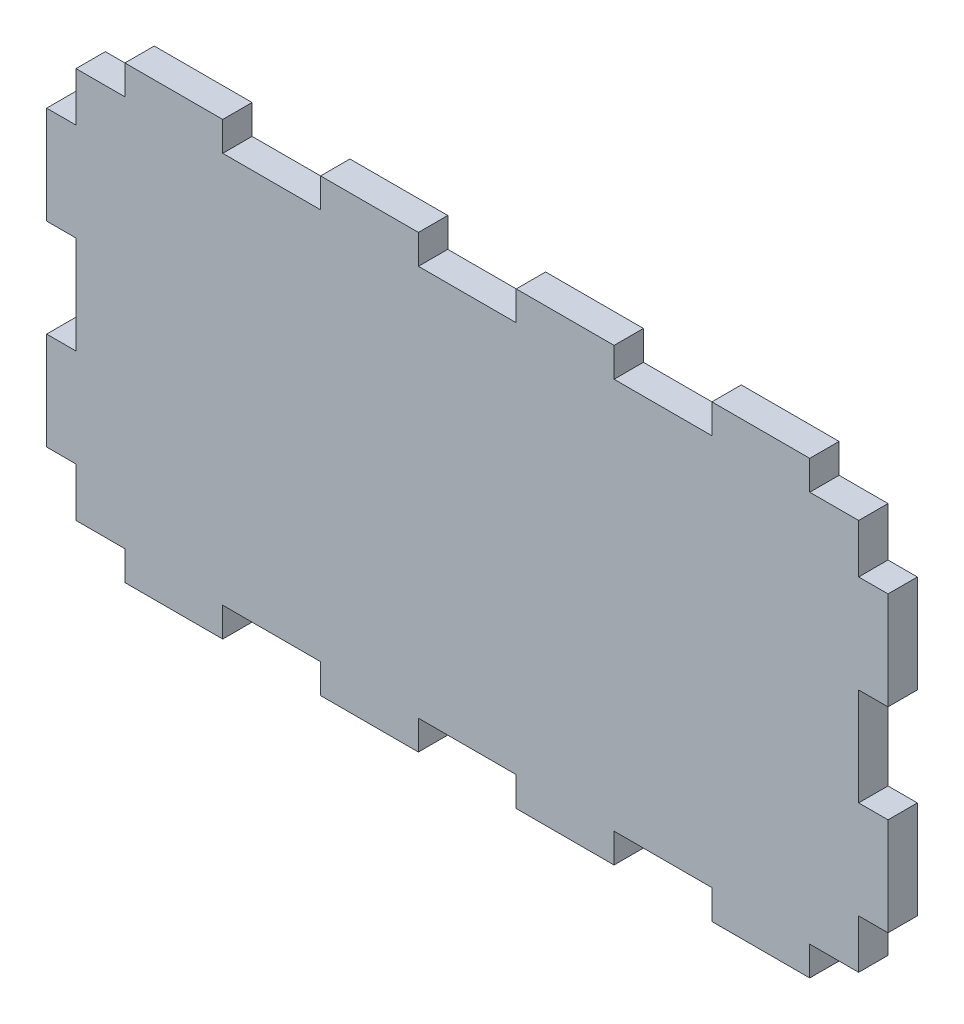
SolidWorks part; units mm, degrees
ref_plane "前视基准面" through (0, 0, 0) normal (0, 0, 1) x (1, 0, 0)
ref_plane "上视基准面" through (0, 0, 0) normal (0, 1, 0) x (1, 0, 0)
ref_plane "右视基准面" through (0, 0, 0) normal (1, 0, 0) x (0, 0, -1)
sketch "草图1" plane through (0, 0, 0) normal (0, 0, 1) x (1, 0, 0)
  line L0 (-15, -20) -> (-15, -23)
  line L1 (-40, 20) -> (-35, 20)
  line L2 (-40, 20) -> (-40, 15)
  line L3 (-40, -20) -> (-35, -20)
  line L4 (40, 20) -> (40, 15)
  line L5 (-40, 20) -> (40, -20) construction
  line L6 (-40, -20) -> (40, 20) construction
  line L8 (-35, -20) -> (-35, -23)
  line L9 (-35, -23) -> (-25, -23)
  line L10 (-25, -20) -> (-25, -23)
  line L12 (-5, -20) -> (-5, -23)
  line L13 (-15, -23) -> (-5, -23)
  line L14 (5, -20) -> (5, -23)
  line L16 (15, -20) -> (15, -23)
  line L17 (5, -23) -> (15, -23)
  line L18 (25, -20) -> (25, -23)
  line L20 (35, -20) -> (35, -23)
  line L21 (25, -23) -> (35, -23)
  line L22 (55, 0) -> (-55, 0) construction
  line L24 (35, 20) -> (35, 23)
  line L25 (25, 23) -> (35, 23)
  line L26 (25, 20) -> (25, 23)
  line L28 (15, 20) -> (15, 23)
  line L29 (5, 23) -> (15, 23)
  line L30 (5, 20) -> (5, 23)
  line L32 (-5, 20) -> (-5, 23)
  line L33 (-15, 23) -> (-5, 23)
  line L34 (-15, 20) -> (-15, 23)
  line L35 (-35, 23) -> (-25, 23)
  line L36 (-25, 20) -> (-25, 23)
  line L37 (-28.5564, 20) -> (-25, 20)
  line L38 (-35, 20) -> (-35, 23)
  line L39 (40, -5) -> (43, -5)
  line L40 (40, 15) -> (43, 15)
  line L42 (40, 5) -> (43, 5)
  line L43 (43, 15) -> (43, 5)
  line L44 (43, -15) -> (43, -5)
  line L45 (40, -15) -> (43, -15)
  line L47 (0, -55) -> (0, 55) construction
  line L49 (-40, -15) -> (-43, -15)
  line L50 (-43, -15) -> (-43, -5)
  line L51 (-40, -5) -> (-43, -5)
  line L52 (-40, 5) -> (-43, 5)
  line L53 (-43, 15) -> (-43, 5)
  line L54 (-40, 15) -> (-43, 15)
  line L56 (-40, 5) -> (-40, -5)
  line L57 (-40, -15) -> (-40, -20)
  line L58 (-25, -20) -> (-15, -20)
  line L59 (-5, -20) -> (5, -20)
  line L60 (15, -20) -> (25, -20)
  line L61 (35, -20) -> (40, -20)
  line L62 (40, -15) -> (40, -20)
  line L63 (40, 5) -> (40, -5)
  line L64 (35, 20) -> (40, 20)
  line L65 (15, 20) -> (25, 20)
  line L66 (-5, 20) -> (5, 20)
  line L67 (-25, 20) -> (-15, 20)
  point P0 (0, 0)
  point P44 (41.5, 15)
  dimension "D1" = 80
  dimension "D2" = 40
  dimension "D3" = 10
  dimension "D4" = 3
  dimension "D5" = 5
  dimension "D7" = 10
  dimension "D8" = 3
  dimension "D9" = 5
  dimension "D6" = 4
extrude "凸台-拉伸1" add sketch "草图1" along normal blind 3
